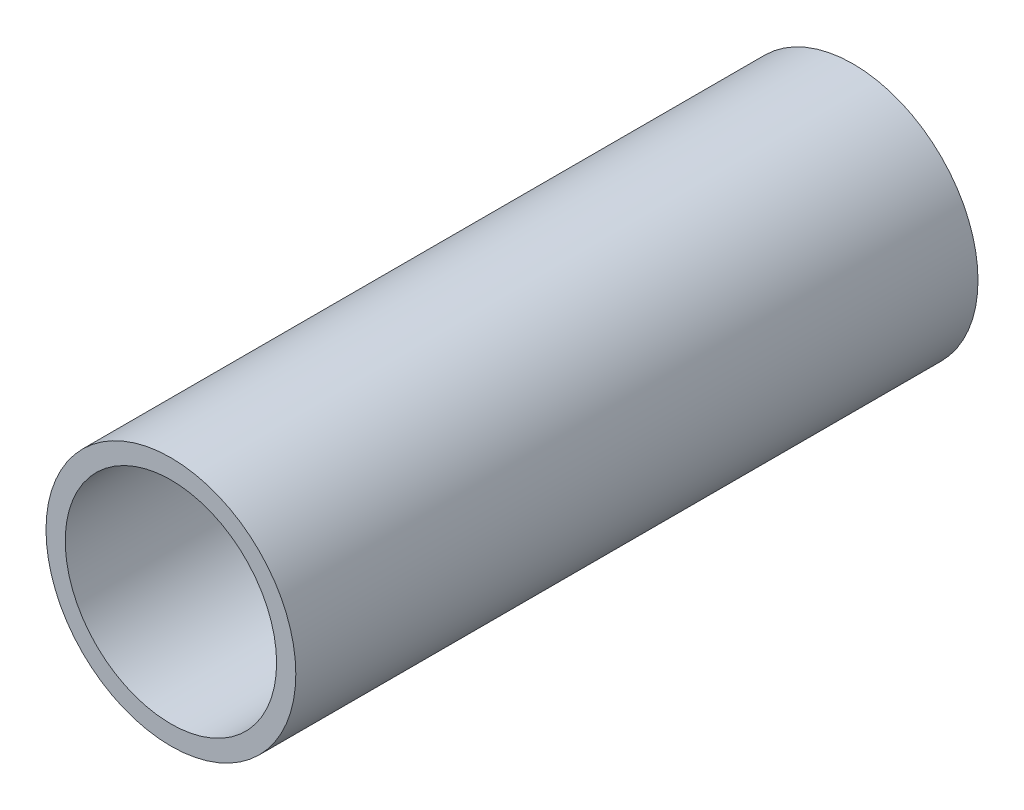
SolidWorks part; units mm, degrees
material "Nylon 101"
ref_plane "Front Plane" through (0, 0, 0) normal (0, 0, 1) x (1, 0, 0)
ref_plane "Top Plane" through (0, 0, 0) normal (0, 1, 0) x (1, 0, 0)
ref_plane "Right Plane" through (0, 0, 0) normal (1, 0, 0) x (0, 0, -1)
sketch "base_sketch" plane through (0, 0, 0) normal (0, 0, 1) x (1, 0, 0)
  circle A0 centre (0, 0) radius 11
  circle A1 centre (0, 0) radius 13
  circle A2 centre (0, 0) radius 10.5 construction
  dimension "D1" = 2
  dimension "D2" = 22
  dimension "D3" = 21
extrude "Boss-Extrude1" add sketch "base_sketch" along normal blind 71
